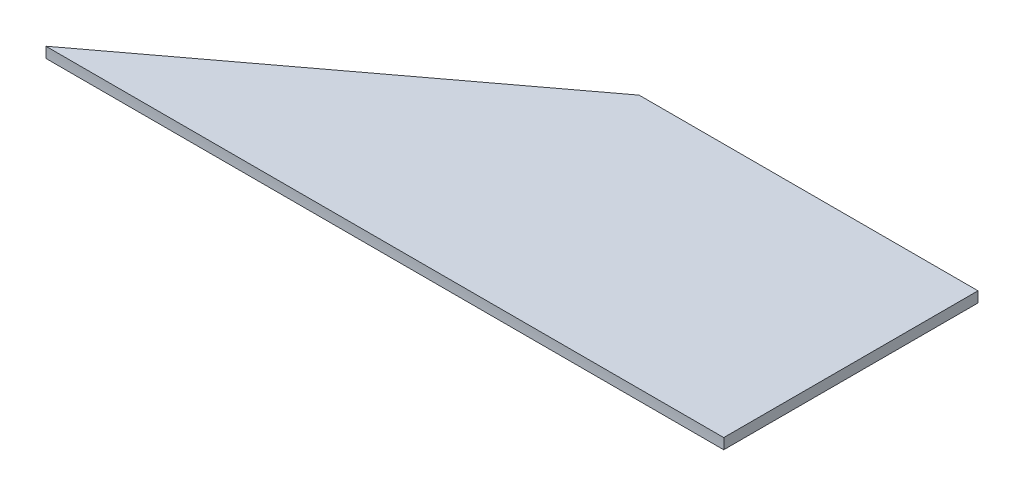
SolidWorks part; units mm, degrees
ref_plane "Front Plane" through (0, 0, 0) normal (0, 0, 1) x (1, 0, 0)
ref_plane "Top Plane" through (0, 0, 0) normal (0, 1, 0) x (1, 0, 0)
ref_plane "Right Plane" through (0, 0, 0) normal (1, 0, 0) x (0, 0, -1)
sketch "Sketch1" plane through (0, 0, 0) normal (0, 1, 0) x (1, 0, 0)
  line L0 (-101.6, 0) -> (101.6, 0)
  line L1 (-101.6, 0) -> (0, 76.2)
  line L2 (0, 76.2) -> (101.6, 76.2)
  line L3 (101.6, 76.2) -> (101.6, 0)
  point P4 (0, 0)
  dimension "D1" = 203.2
  dimension "D2" = 101.6
  dimension "D3" = 101.6
  dimension "D4" = 76.2
extrude "Boss-Extrude1" add sketch "Sketch1" along normal mid plane 3.175
sketch "Sketch2" plane through (0, 0, 0) normal (1, 0, 0) x (0, 0, -1)
  line L0 (0, 0) -> (-39.624, 0)
  line L1 (0, 1.5875) -> (-0.0318, 1.5875)
  line L2 (0, -1.5875) -> (-0.008, -0.7937)
  line L3 (0, 1.5875) -> (0, -1.5875)
  line L4 (0, -1.5875) -> (-0.0318, -1.5875)
  circle A0 centre (-39.624, 0) radius 39.624
  point P9 (0, 0)
  dimension "D1" = 79.248
extrude "Boss-Extrude2" add sketch "Sketch2" along normal mid plane 203.2 contours A0 L4 L2 | A0 L2 L3 | A0 L3 L1
ref_plane "Plane2" through (0, 1.525, 0) normal (0, 1, 0) x (1, 0, 0)
